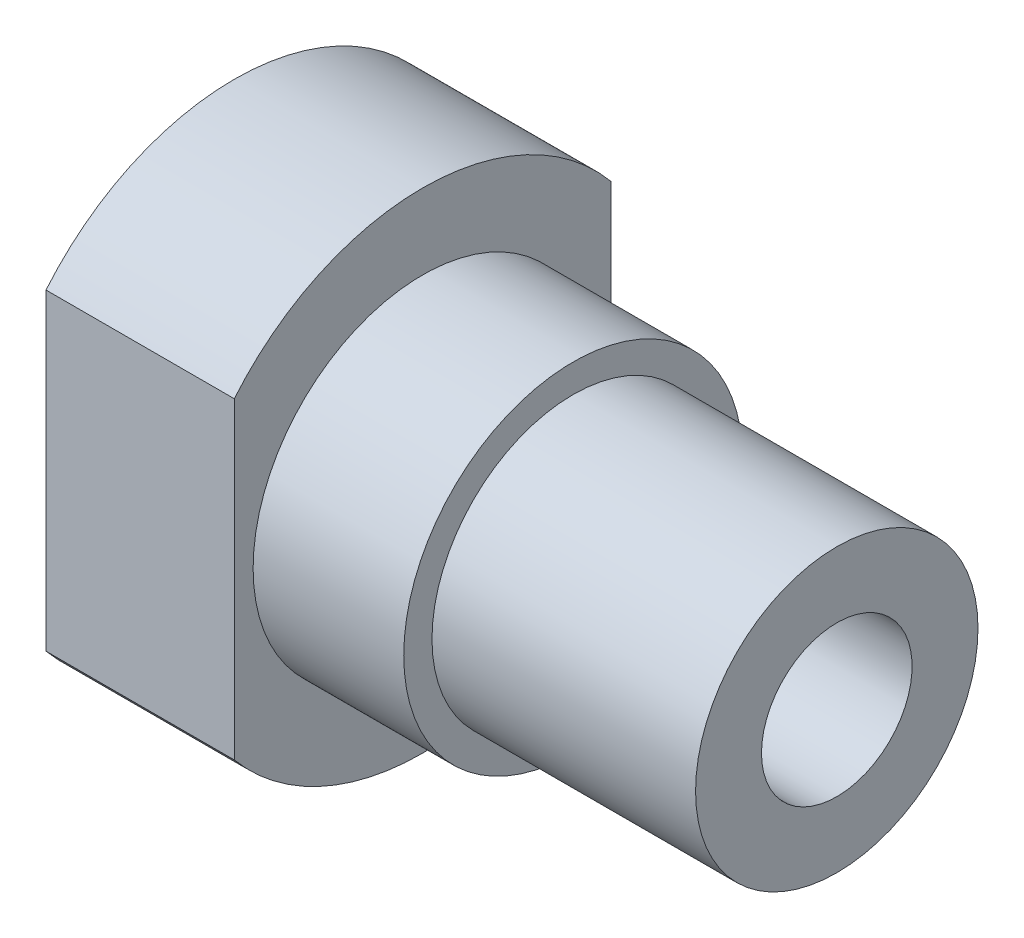
SolidWorks part; units mm, degrees
material "Сталь"
ref_plane "Спереди" through (0, 0, 0) normal (0, 0, 1) x (1, 0, 0)
ref_plane "Сверху" through (0, 0, 0) normal (0, 1, 0) x (1, 0, 0)
ref_plane "Справа" through (0, 0, 0) normal (1, 0, 0) x (0, 0, -1)
sketch "Эскиз1" plane through (0, 0, 0) normal (0, 0, 1) x (1, 0, 0)
  line L0 (0, 0) -> (21.9848, 0) construction
  line L1 (0, 4) -> (2, 4)
  line L2 (2, 4) -> (2, 2.5)
  line L3 (2, 2.5) -> (6, 2.5)
  line L4 (6, 2.5) -> (6, 2)
  line L5 (6, 2) -> (16, 2)
  line L6 (16, 2) -> (16, 3.75)
  line L7 (16, 3.75) -> (9, 3.75)
  line L8 (9, 3.75) -> (9, 4.5)
  line L9 (9, 4.5) -> (5, 4.5)
  line L10 (5, 4.5) -> (5, 6.5)
  line L11 (5, 6.5) -> (0, 6.5)
  line L12 (0, 6.5) -> (0, 4)
  dimension "D1" = 8
  dimension "D2" = 5
  dimension "D3" = 4
  dimension "D4" = 2
  dimension "D5" = 4
  dimension "D6" = 10
  dimension "D7" = 7.5
  dimension "D8" = 7
  dimension "D9" = 4
  dimension "D10" = 9
  dimension "D11" = 13
revolve "Повернуть1" add sketch "Эскиз1" angle 360 about L0
sketch "Эскиз2" plane through (5, 0, 0) normal (1, 0, 0) x (0, 0, -1)
  line L1 (5, -4.1533) -> (-5, -4.1533)
  line L2 (5, -4.1533) -> (5, 4.1533)
  line L3 (5, 4.1533) -> (-5, 4.1533)
  line L4 (-5, -4.1533) -> (-5, 4.1533)
  line L5 (5, -4.1533) -> (-5, 4.1533) construction
  line L6 (5, 4.1533) -> (-5, -4.1533) construction
  circle A1 centre (0, 0) radius 6.5
  circle A2 centre (0, 0) radius 6.5
  circle M3 centre (0, 0) radius 6.5
  dimension "D2" = 1.5
  dimension "D1" = 0
extrude "Вырез-Вытянуть1" cut sketch "Эскиз2" against normal through all contours L4 M3 | L2 M3
